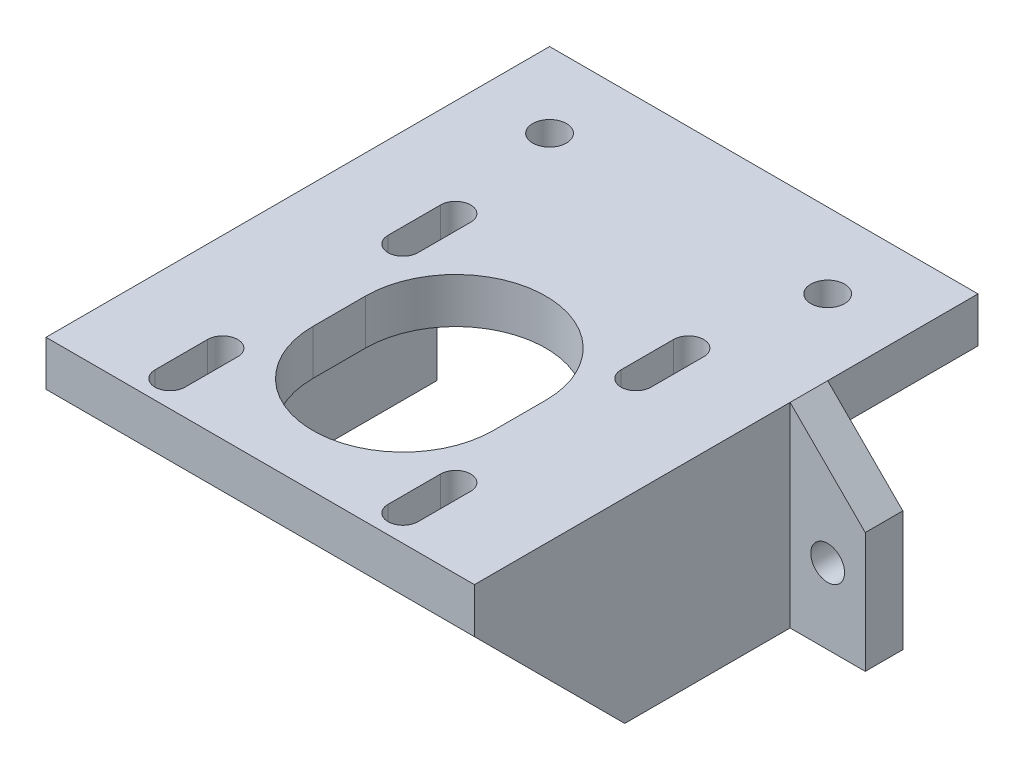
SolidWorks part; units mm, degrees
ref_plane "Front Plane" through (0, 0, 0) normal (0, 0, 1) x (1, 0, 0)
ref_plane "Top Plane" through (0, 0, 0) normal (0, 1, 0) x (1, 0, 0)
ref_plane "Right Plane" through (0, 0, 0) normal (1, 0, 0) x (0, 0, -1)
sketch "Sketch1" plane through (0, 0, 0) normal (0, 0, 1) x (1, 0, 0)
  line L1 (-28.5, 3) -> (28.5, 3)
  line L2 (-28.5, 3) -> (-28.5, -3)
  line L3 (-28.5, -3) -> (28.5, -3)
  line L4 (28.5, 3) -> (28.5, -3)
  line L5 (-28.5, 3) -> (28.5, -3) construction
  line L6 (-28.5, -3) -> (28.5, 3) construction
  point P0 (0, 0)
  dimension "D1" = 57
  dimension "D2" = 6
extrude "Boss-Extrude1" add sketch "Sketch1" along normal blind 50
sketch "Sketch3" plane through (0, 3, 0) normal (0, 1, 0) x (1, 0, 0)
  line L0 (28.5, 0) -> (-28.5, 0) construction
  line L1 (-15.5, -8.5) -> (-15.5, -15.5) construction
  line L2 (-13.5, -8.5) -> (-13.5, -15.5)
  line L3 (-17.5, -8.5) -> (-17.5, -15.5)
  line L4 (-15.5, -39.5) -> (-15.5, -46.5) construction
  line L5 (-13.5, -39.5) -> (-13.5, -46.5)
  line L6 (-17.5, -39.5) -> (-17.5, -46.5)
  line L7 (15.5, -39.5) -> (15.5, -46.5) construction
  line L8 (17.5, -39.5) -> (17.5, -46.5)
  line L9 (13.5, -39.5) -> (13.5, -46.5)
  line L10 (15.5, -8.5) -> (15.5, -15.5) construction
  line L11 (17.5, -8.5) -> (17.5, -15.5)
  line L12 (13.5, -8.5) -> (13.5, -15.5)
  line L13 (0, -24) -> (0, -31) construction
  line L14 (12, -24) -> (12, -31)
  line L15 (-12, -24) -> (-12, -31)
  arc A0 (-13.5, -8.5) -> (-17.5, -8.5) centre (-15.5, -8.5) ccw
  arc A1 (-17.5, -15.5) -> (-13.5, -15.5) centre (-15.5, -15.5) ccw
  arc A2 (-13.5, -39.5) -> (-17.5, -39.5) centre (-15.5, -39.5) ccw
  arc A3 (-17.5, -46.5) -> (-13.5, -46.5) centre (-15.5, -46.5) ccw
  arc A4 (17.5, -39.5) -> (13.5, -39.5) centre (15.5, -39.5) ccw
  circle A5 centre (0, -24) radius 12 construction
  circle A6 centre (-15.5, -8.5) radius 2 construction
  circle A7 centre (15.5, -8.5) radius 2 construction
  circle A8 centre (15.5, -39.5) radius 2 construction
  circle A9 centre (-15.5, -39.5) radius 2 construction
  arc A10 (13.5, -46.5) -> (17.5, -46.5) centre (15.5, -46.5) ccw
  arc A11 (17.5, -8.5) -> (13.5, -8.5) centre (15.5, -8.5) ccw
  arc A12 (13.5, -15.5) -> (17.5, -15.5) centre (15.5, -15.5) ccw
  arc A13 (12, -24) -> (-12, -24) centre (0, -24) ccw
  arc A14 (-12, -31) -> (12, -31) centre (0, -31) ccw
  point P5 (-15.5, -12)
  point P18 (-15.5, -43)
  point P25 (15.5, -43)
  point P31 (15.5, -12)
  point P37 (0, -27.5)
  dimension "D1" = 24
  dimension "D2" = 31
  dimension "D7" = 4
  dimension "D3" = 31
  dimension "D4" = 31
  dimension "D5" = 8.5
  dimension "D6" = 15.5
  dimension "D8" = 24
  dimension "D9" = 7
extrude "Cut-Extrude2" cut sketch "Sketch3" against normal blind 10
sketch "Sketch4" plane through (0, 0, 0) normal (0, 0, -1) x (-1, 0, 0)
  line L0 (28.5, 3) -> (28.5, -3) construction
  line L1 (28.5, 3) -> (-28.5, 3)
  line L2 (28.5, 3) -> (28.5, -3)
  line L3 (28.5, -3) -> (-28.5, -3)
  line L4 (-28.5, 3) -> (-28.5, -3)
  point P6 (-28.5, 25)
  dimension "D1" = 6
extrude "Boss-Extrude2" add sketch "Sketch4" along normal blind 17
sketch "Sketch6" plane through (0, 3, 0) normal (0, 1, 0) x (1, 0, 0)
  line L0 (-28.5, 17) -> (28.5, 17) construction
  line L1 (-28.5, -50) -> (-28.5, 17) construction
  line L2 (28.5, -50) -> (28.5, 17) construction
  line L3 (-28.5, 17) -> (28.5, 17) construction
  circle A0 centre (-18.5, 7) radius 2.25
  circle A1 centre (18.5, 7) radius 2.25
  dimension "D2" = 4.5
  dimension "D4" = 10
  dimension "D5" = 10
  dimension "D1" = 10
  dimension "D3" = 10
extrude "Cut-Extrude3" cut sketch "Sketch6" against normal blind 20
sketch "Sketch8" plane through (0, -3, 0) normal (0, -1, 0) x (1, 0, 0)
  line L0 (28.5, -17) -> (-28.5, -17) construction
  line L1 (-28.5, 50) -> (-23.5, 50)
  line L2 (-28.5, 50) -> (-28.5, 3)
  line L3 (-28.5, 3) -> (-23.5, 3)
  line L4 (-23.5, 50) -> (-23.5, 3)
  line L5 (28.5, 50) -> (23.5, 50)
  line L6 (28.5, 50) -> (28.5, 3)
  line L7 (28.5, 3) -> (23.5, 3)
  line L8 (23.5, 50) -> (23.5, 3)
  dimension "D1" = 5
  dimension "D2" = 5
  dimension "D3" = 20
extrude "Boss-Extrude4" add sketch "Sketch8" along normal blind 20
chamfer "Chamfer1" distance 20 angle 45 2 edges at (26, -23, 50) (-26, -23, 50)
sketch "Sketch9" plane through (-28.5, 0, 0) normal (-1, 0, 0) x (0, 0, 1)
  line L0 (50, 3) -> (-17, 3) construction
  line L1 (3, -23) -> (8, -23)
  line L2 (3, -23) -> (3, 3)
  line L3 (3, 3) -> (8, 3)
  line L4 (8, -23) -> (8, 3)
  dimension "D1" = 5
extrude "Boss-Extrude5" add sketch "Sketch9" along normal blind 10
sketch "Sketch10" plane through (28.5, 0, 0) normal (1, 0, 0) x (0, 0, -1)
  line L0 (-50, 3) -> (17, 3) construction
  line L2 (-3, -23) -> (-8, -23)
  line L3 (-3, -23) -> (-3, 3)
  line L4 (-3, 3) -> (-8, 3)
  line L5 (-8, -23) -> (-8, 3)
  dimension "D1" = 5
extrude "Boss-Extrude6" add sketch "Sketch10" along normal blind 10
chamfer "Chamfer2" distance 10 angle 45 2 edges at (38.5, 3, 5.5) (-38.5, 3, 5.5)
sketch "Sketch11" plane through (0, 0, 8) normal (0, 0, 1) x (1, 0, 0)
  line L0 (-38.5, -23) -> (-38.5, -7) construction
  line L1 (-38.5, -23) -> (-28.5, -23) construction
  line L2 (38.5, -7) -> (38.5, -23) construction
  circle A0 centre (-33.5, -13) radius 2.25
  circle A1 centre (33.5, -13) radius 2.25
  point P10 (0, 0)
  dimension "D1" = 4.5
  dimension "D3" = 10
  dimension "D2" = 5
  dimension "D4" = 5
extrude "Cut-Extrude4" cut sketch "Sketch11" against normal blind 10
